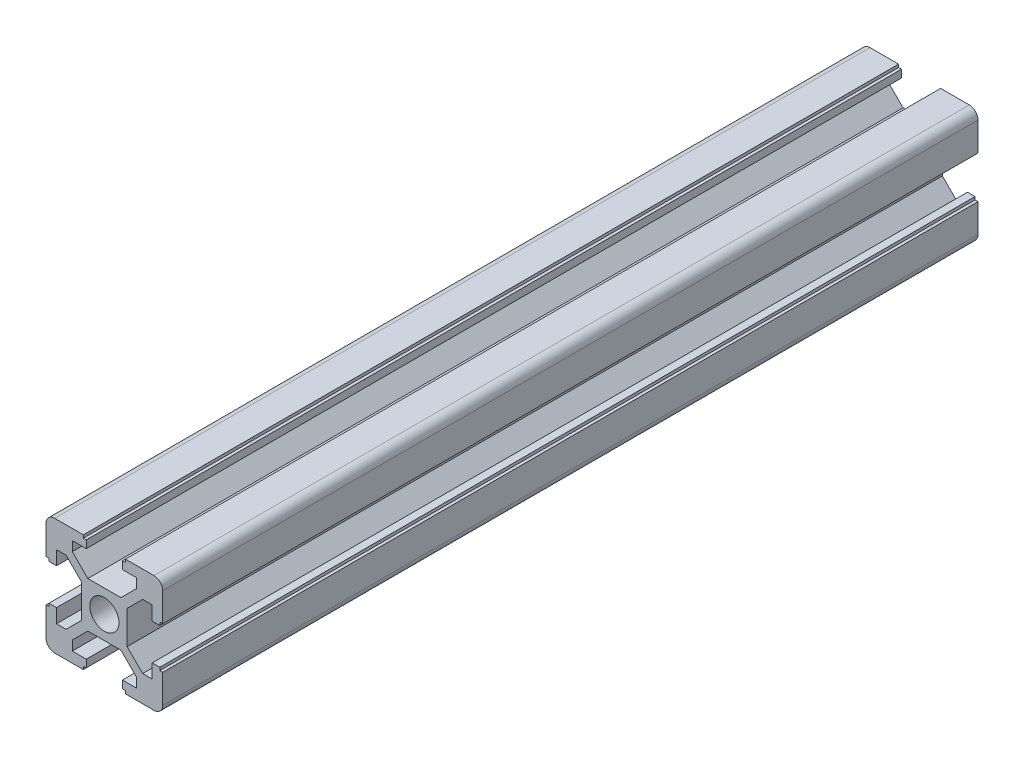
SolidWorks part; units mm, degrees
material "6061-T6 (SS)"
ref_plane "Front Plane" through (0, 0, 0) normal (0, 0, 1) x (1, 0, 0)
ref_plane "Top Plane" through (0, 0, 0) normal (0, 1, 0) x (1, 0, 0)
ref_plane "Right Plane" through (0, 0, 0) normal (1, 0, 0) x (0, 0, -1)
sketch "Sketch1" plane through (0, 0, 0) normal (0, 0, 1) x (1, 0, 0)
  line L0 (0, 12.2813) -> (0, -11.8053) construction
  line L1 (-10, 0) -> (10.7981, 0) construction
  line L2 (-10, -3.6) -> (-10, -8.5)
  line L3 (-3.6, -10) -> (-8.5, -10)
  line L4 (-3.9, 2.8393) -> (-3.9, -2.8393)
  line L5 (-3.9, -2.8393) -> (-6.5607, -5.5)
  line L6 (-3.6, -10) -> (-3.6, -9.5)
  line L7 (-3.6, -9.5) -> (-3.1, -9.5)
  line L8 (-10, -3.6) -> (-9.5, -3.6)
  line L9 (-9.5, -3.6) -> (-9.5, -3.1)
  line L10 (-9.5, -3.1) -> (-8.2, -3.1)
  line L11 (-8.2, -3.1) -> (-8.2, -5.5)
  line L12 (-8.2, -5.5) -> (-6.5607, -5.5)
  line L13 (-3.1, -9.5) -> (-3.1, -8.2)
  line L14 (-3.1, -8.2) -> (-5.5, -8.2)
  line L15 (-5.5, -8.2) -> (-5.5, -6.5607)
  line L16 (-2.8393, -3.9) -> (-5.5, -6.5607)
  line L17 (0, -3.9) -> (-2.8393, -3.9)
  line L18 (-10, -10) -> (0, 0) construction
  line L19 (0, -3.9) -> (2.8393, -3.9)
  line L20 (2.8393, -3.9) -> (5.5, -6.5607)
  line L21 (5.5, -8.2) -> (5.5, -6.5607)
  line L22 (3.1, -8.2) -> (5.5, -8.2)
  line L23 (3.1, -9.5) -> (3.1, -8.2)
  line L24 (8.2, -5.5) -> (6.5607, -5.5)
  line L25 (8.2, -3.1) -> (8.2, -5.5)
  line L26 (9.5, -3.1) -> (8.2, -3.1)
  line L27 (9.5, -3.6) -> (9.5, -3.1)
  line L28 (10, -3.6) -> (9.5, -3.6)
  line L29 (3.6, -9.5) -> (3.1, -9.5)
  line L30 (3.6, -10) -> (3.6, -9.5)
  line L31 (3.9, -2.8393) -> (6.5607, -5.5)
  line L32 (3.6, -10) -> (8.5, -10)
  line L33 (10, -3.6) -> (10, -8.5)
  line L34 (3.9, 2.8393) -> (3.9, -2.8393)
  line L36 (10, 3.6) -> (10, 8.5)
  line L37 (3.6, 10) -> (8.5, 10)
  line L38 (3.9, 2.8393) -> (6.5607, 5.5)
  line L39 (3.6, 10) -> (3.6, 9.5)
  line L40 (3.6, 9.5) -> (3.1, 9.5)
  line L41 (10, 3.6) -> (9.5, 3.6)
  line L42 (9.5, 3.6) -> (9.5, 3.1)
  line L43 (9.5, 3.1) -> (8.2, 3.1)
  line L44 (8.2, 3.1) -> (8.2, 5.5)
  line L45 (8.2, 5.5) -> (6.5607, 5.5)
  line L46 (3.1, 9.5) -> (3.1, 8.2)
  line L47 (3.1, 8.2) -> (5.5, 8.2)
  line L48 (5.5, 8.2) -> (5.5, 6.5607)
  line L49 (2.8393, 3.9) -> (5.5, 6.5607)
  line L50 (0, 3.9) -> (2.8393, 3.9)
  line L51 (0, 3.9) -> (-2.8393, 3.9)
  line L52 (-2.8393, 3.9) -> (-5.5, 6.5607)
  line L53 (-5.5, 8.2) -> (-5.5, 6.5607)
  line L54 (-3.1, 8.2) -> (-5.5, 8.2)
  line L55 (-3.1, 9.5) -> (-3.1, 8.2)
  line L56 (-8.2, 5.5) -> (-6.5607, 5.5)
  line L57 (-8.2, 3.1) -> (-8.2, 5.5)
  line L58 (-9.5, 3.1) -> (-8.2, 3.1)
  line L59 (-9.5, 3.6) -> (-9.5, 3.1)
  line L60 (-10, 3.6) -> (-9.5, 3.6)
  line L61 (-3.6, 9.5) -> (-3.1, 9.5)
  line L62 (-3.6, 10) -> (-3.6, 9.5)
  line L63 (-3.9, 2.8393) -> (-6.5607, 5.5)
  line L64 (-3.6, 10) -> (-8.5, 10)
  line L65 (-10, 3.6) -> (-10, 8.5)
  circle A0 centre (0, 0) radius 2.5
  arc A1 (10, 8.5) -> (8.5, 10) centre (8.5, 8.5) ccw
  arc A2 (8.5, -10) -> (10, -8.5) centre (8.5, -8.5) ccw
  arc A3 (-10, -8.5) -> (-8.5, -10) centre (-8.5, -8.5) ccw
  arc A4 (-10, 8.5) -> (-8.5, 10) centre (-8.5, 8.5) cw
  point P43 (3.9, 0)
  point P73 (-3.9, 0)
  point P74 (10, 10)
  point P77 (10, -10)
  point P83 (-10, 10)
  dimension "D1" = 5
  dimension "D9" = 1.5
  dimension "D2" = 20
  dimension "D3" = 11
  dimension "D4" = 7.2
  dimension "D5" = 6.2
  dimension "D6" = 1.5
  dimension "D7" = 6.1
  dimension "D8" = 1.8
extrude "Boss-Extrude1" add sketch "Sketch1" along normal blind 139.7
sketch "Sketch2" plane through (0, 0, 0) normal (1, 0, 0) x (0, 0, -1)
  line L0 (-69.85, 10) -> (-69.85, -10) construction
  line L1 (-139.7, 10) -> (0, 10) construction
  line L2 (-139.7, -10) -> (0, -10) construction
  line L4 (0, 10) -> (0, -10) construction
  line L6 (209.55, 0) -> (-222.25, 0) construction
  circle A0 centre (209.55, 0) radius 3.429
  circle A1 centre (-222.25, 0) radius 3.429
  point P8 (-69.85, 0)
  dimension "D1" = 6.858
  dimension "D2" = 279.4
  dimension "D3" = 152.4
extrude "Cut-Extrude1" [suppressed] cut sketch "Sketch2" against normal through all both and the other way through all
equation "\"L\"= 0"
